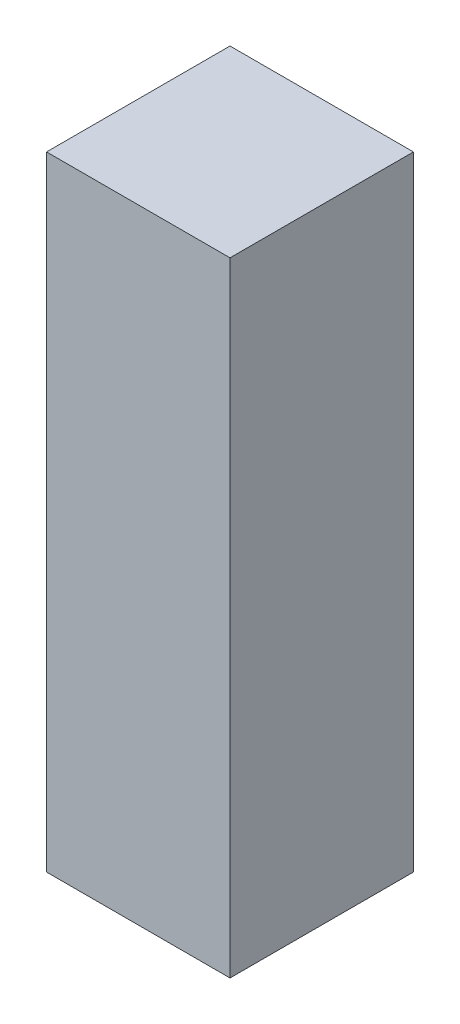
SolidWorks part; units mm, degrees
ref_plane "Front Plane" through (0, 0, 0) normal (0, 0, 1) x (1, 0, 0)
ref_plane "Top Plane" through (0, 0, 0) normal (0, 1, 0) x (1, 0, 0)
ref_plane "Right Plane" through (0, 0, 0) normal (1, 0, 0) x (0, 0, -1)
sketch "Sketch1" plane through (0, 0, 0) normal (0, 1, 0) x (1, 0, 0)
  line L0 (-13, 13) -> (13, 13)
  line L1 (-15, -15) -> (15, -15)
  line L2 (-15, -15) -> (-15, 15)
  line L3 (-15, 15) -> (15, 15)
  line L4 (15, -15) -> (15, 15)
  line L5 (-15, -15) -> (15, 15) construction
  line L6 (-15, 15) -> (15, -15) construction
  line L7 (13, -13) -> (13, 13)
  line L8 (-13, -13) -> (13, -13)
  line L9 (-13, -13) -> (-13, 13)
  point P0 (0, 0)
  dimension "D1" = 30
  dimension "D2" = 2
extrude "Boss-Extrude1" add sketch "Sketch1" along normal blind 100
sketch "Sketch2" plane through (0, 100, 0) normal (0, 1, 0) x (1, 0, 0)
  line L1 (-15, 15) -> (15, 15)
  line L2 (-15, 15) -> (-15, -15)
  line L3 (-15, -15) -> (15, -15)
  line L4 (15, 15) -> (15, -15)
extrude "Boss-Extrude2" add sketch "Sketch2" along normal blind 1
sketch "Sketch3" plane through (0, 0, 0) normal (0, -1, 0) x (1, 0, 0)
  line L1 (-15, 15) -> (15, 15)
  line L2 (-15, 15) -> (-15, -15)
  line L3 (-15, -15) -> (15, -15)
  line L4 (15, 15) -> (15, -15)
extrude "Boss-Extrude3" add sketch "Sketch3" along normal blind 1
